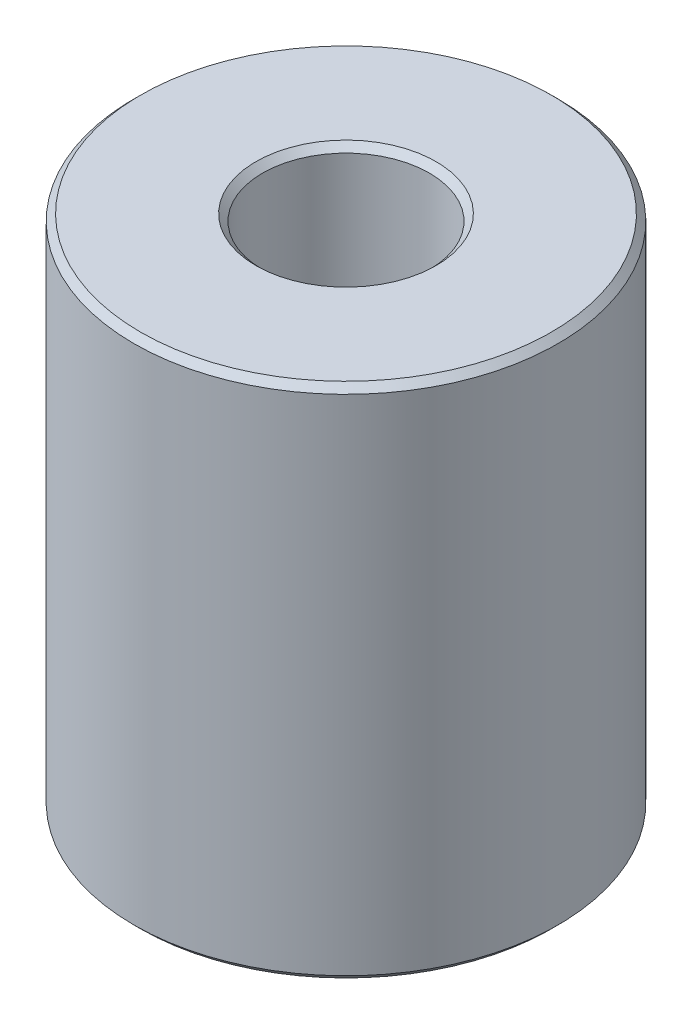
SolidWorks part; units mm, degrees
ref_plane "Plano frontal" through (0, 0, 0) normal (0, 0, 1) x (1, 0, 0)
ref_plane "Plano superior" through (0, 0, 0) normal (0, 1, 0) x (1, 0, 0)
ref_plane "Plano direito" through (0, 0, 0) normal (1, 0, 0) x (0, 0, -1)
ref_plane "Plano1" through (0, 0, 0) normal (0, 0, -1) x (-1, 0, 0)
sketch "Esboço1" plane through (0, 0, 0) normal (0, 0, -1) x (-1, 0, 0)
  line L0 (-6.8, 0) -> (-6.3, 0.5)
  line L1 (-6.3, 0.5) -> (-6.3, 38.5)
  line L2 (-6.3, 38.5) -> (-6.8, 39)
  line L3 (-6.8, 39) -> (-15.5, 39)
  line L4 (-15.5, 39) -> (-16, 38.5)
  line L5 (-16, 38.5) -> (-16, 0.5)
  line L6 (-16, 0.5) -> (-15.5, 0)
  line L7 (-15.5, 0) -> (-6.8, 0)
  line L8 (0, 0) -> (0, 39) construction
revolve "Revolução1" add sketch "Esboço1" angle 360 about L8
